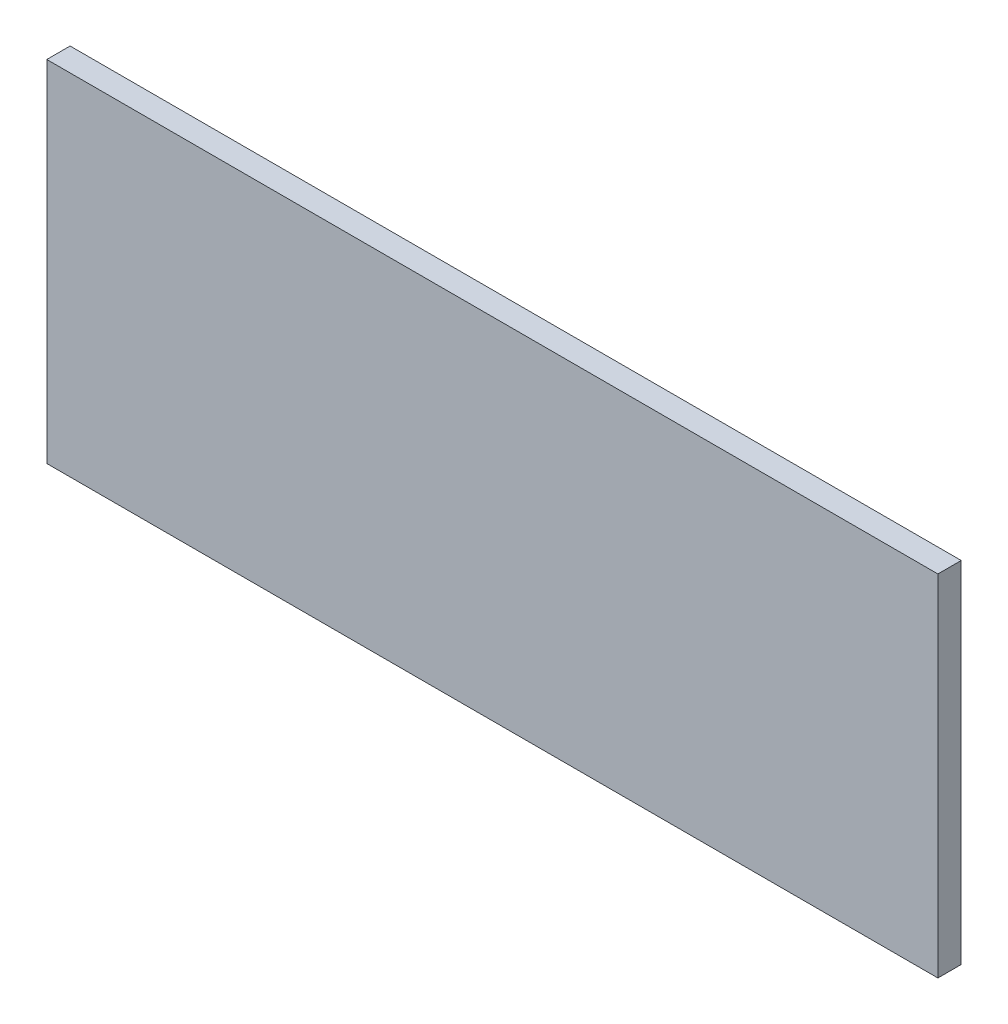
SolidWorks part; units mm, degrees
ref_plane "Front Plane" through (0, 0, 0) normal (0, 0, 1) x (1, 0, 0)
ref_plane "Top Plane" through (0, 0, 0) normal (0, 1, 0) x (1, 0, 0)
ref_plane "Right Plane" through (0, 0, 0) normal (1, 0, 0) x (0, 0, -1)
sketch "Sketch1" plane through (0, 0, 0) normal (0, 0, 1) x (1, 0, 0)
  line L1 (-191, 75) -> (191, 75)
  line L2 (-191, 75) -> (-191, -75)
  line L3 (-191, -75) -> (191, -75)
  line L4 (191, 75) -> (191, -75)
  line L5 (-191, 75) -> (191, -75) construction
  line L6 (-191, -75) -> (191, 75) construction
  point P0 (0, 0)
  dimension "D1" = 382
  dimension "D2" = 150
extrude "Boss-Extrude1" add sketch "Sketch1" along normal blind 10
